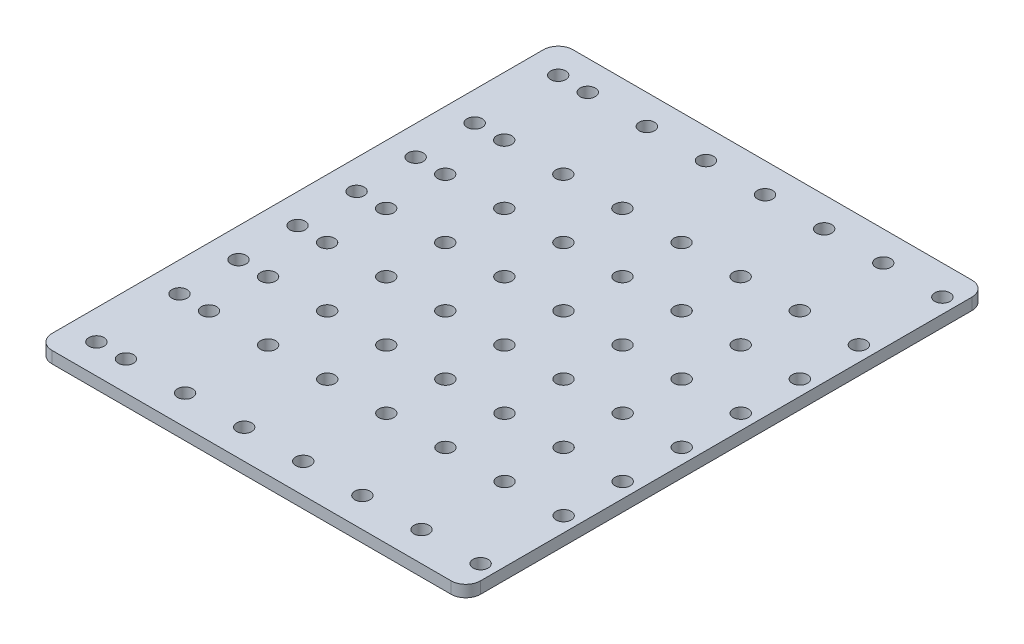
SolidWorks part; units mm, degrees
ref_plane "Front Plane" through (0, 0, 0) normal (0, 0, 1) x (1, 0, 0)
ref_plane "Top Plane" through (0, 0, 0) normal (0, 1, 0) x (1, 0, 0)
ref_plane "Right Plane" through (0, 0, 0) normal (1, 0, 0) x (0, 0, -1)
sketch "Sketch1" plane through (0, 0, 0) normal (0, 1, 0) x (1, 0, 0)
  line L0 (54, -9.0119) -> (54, -50009.0119) construction
  line L1 (-58, 70.5) -> (58, 70.5)
  line L2 (-58, 70.5) -> (-58, -70.5)
  line L3 (-58, -70.5) -> (58, -70.5)
  line L4 (58, 70.5) -> (58, -70.5)
  line L5 (-58, 70.5) -> (58, -70.5) construction
  line L6 (-58, -70.5) -> (58, 70.5) construction
  line L7 (17.5855, -62.5) -> (50017.5855, -62.5) construction
  line L8 (54, -62.5) -> (38, -62.5) construction
  line L9 (0, 0) -> (50000, 0) construction
  line L10 (-45.6818, -56) -> (49954.3182, -56) construction
  line L11 (-42, -56) -> (-26, -56) construction
  line L12 (-42, -62.5) -> (-50, -62.5) construction
  line L13 (-42.1091, 40) -> (-50.1091, 40) construction
  circle A0 centre (54, -62.5) radius 2.05
  circle A1 centre (38, -62.5) radius 2.05
  circle A2 centre (22, -62.5) radius 2.05
  circle A3 centre (6, -62.5) radius 2.05
  circle A4 centre (-10, -62.5) radius 2.05
  circle A5 centre (-26, -62.5) radius 2.05
  circle A6 centre (-42, -62.5) radius 2.05
  circle A7 centre (-42, 62.5) radius 2.05
  circle A8 centre (-26, 62.5) radius 2.05
  circle A9 centre (-10, 62.5) radius 2.05
  circle A10 centre (6, 62.5) radius 2.05
  circle A11 centre (22, 62.5) radius 2.05
  circle A12 centre (38, 62.5) radius 2.05
  circle A13 centre (54, 62.5) radius 2.05
  circle A14 centre (-42, -56) radius 2.05 construction
  circle A15 centre (-26, -56) radius 2.05 construction
  circle A16 centre (-10, -56) radius 2.05 construction
  circle A17 centre (6, -56) radius 2.05 construction
  circle A18 centre (22, -56) radius 2.05 construction
  circle A19 centre (38, -56) radius 2.05 construction
  circle A20 centre (54, -56) radius 2.05 construction
  circle A21 centre (-26.0182, -40) radius 2.05
  circle A22 centre (-10.0182, -40) radius 2.05
  circle A23 centre (5.9818, -40) radius 2.05
  circle A24 centre (21.9818, -40) radius 2.05
  circle A25 centre (37.9818, -40) radius 2.05
  circle A26 centre (53.9818, -40) radius 2.05
  circle A27 centre (-26.0364, -24) radius 2.05
  circle A28 centre (-10.0364, -24) radius 2.05
  circle A29 centre (5.9636, -24) radius 2.05
  circle A30 centre (21.9636, -24) radius 2.05
  circle A31 centre (37.9636, -24) radius 2.05
  circle A32 centre (53.9636, -24) radius 2.05
  circle A33 centre (-26.0546, -8) radius 2.05
  circle A34 centre (-10.0546, -8) radius 2.05
  circle A35 centre (5.9454, -8) radius 2.05
  circle A36 centre (21.9454, -8) radius 2.05
  circle A37 centre (37.9454, -8) radius 2.05
  circle A38 centre (53.9454, -8) radius 2.05
  circle A39 centre (-26.0728, 8) radius 2.05
  circle A40 centre (-10.0728, 8) radius 2.05
  circle A41 centre (5.9272, 8) radius 2.05
  circle A42 centre (21.9272, 8) radius 2.05
  circle A43 centre (37.9272, 8) radius 2.05
  circle A44 centre (53.9272, 8) radius 2.05
  circle A45 centre (-26.091, 24) radius 2.05
  circle A46 centre (-10.091, 24) radius 2.05
  circle A47 centre (5.909, 24) radius 2.05
  circle A48 centre (21.909, 24) radius 2.05
  circle A49 centre (37.909, 24) radius 2.05
  circle A50 centre (53.909, 24) radius 2.05
  circle A51 centre (-26.1091, 40) radius 2.05
  circle A52 centre (-10.1091, 40) radius 2.05
  circle A53 centre (5.8909, 40) radius 2.05
  circle A54 centre (21.8909, 40) radius 2.05
  circle A55 centre (37.8909, 40) radius 2.05
  circle A56 centre (53.8909, 40) radius 2.05
  circle A57 centre (-26.1273, 56) radius 2.05 construction
  circle A58 centre (-10.1273, 56) radius 2.05 construction
  circle A59 centre (5.8727, 56) radius 2.05 construction
  circle A60 centre (21.8727, 56) radius 2.05 construction
  circle A61 centre (37.8727, 56) radius 2.05 construction
  circle A62 centre (53.8727, 56) radius 2.05 construction
  circle A63 centre (-42.0182, -40) radius 2.05
  circle A64 centre (-42.0364, -24) radius 2.05
  circle A65 centre (-42.0546, -8) radius 2.05
  circle A66 centre (-42.0728, 8) radius 2.05
  circle A67 centre (-42.091, 24) radius 2.05
  circle A68 centre (-42.1091, 40) radius 2.05
  circle A69 centre (-42.1273, 56) radius 2.05 construction
  circle A70 centre (-50, -62.5) radius 2.05
  circle A71 centre (-50, -56) radius 2.05 construction
  circle A72 centre (-50.0182, -40) radius 2.05
  circle A73 centre (-50.0364, -24) radius 2.05
  circle A74 centre (-50.0546, -8) radius 2.05
  circle A75 centre (-50.0728, 8) radius 2.05
  circle A76 centre (-50.091, 24) radius 2.05
  circle A77 centre (-50.1273, 56) radius 2.05 construction
  circle A78 centre (-50, 62.5) radius 2.05
  circle A79 centre (-50.1091, 40) radius 2.05
  point P0 (0, 0)
  dimension "D5" = 4.1
  dimension "D1" = 141
  dimension "D2" = 116
  dimension "D3" = 8
  dimension "D4" = 4
  dimension "D7" = 16
  dimension "D8" = 6.5
  dimension "D11" = 16
  dimension "D13" = 8
  dimension "D15" = 8
  dimension "D6" = 7
  dimension "D9" = 7
  dimension "D10" = 8
  dimension "D12" = 2
  dimension "D14" = 2
extrude "Boss-Extrude1" add sketch "Sketch1" along normal blind 3.175
fillet "Fillet1" radius 4 4 edges at (58, 1.5875, -70.5) (-58, 1.5875, -70.5) (-58, 1.5875, 70.5) (58, 1.5875, 70.5)
equation "\"h\"= 141mm"
equation "\"w\"= 14 * 8 + 4"
equation "\"D1@Sketch1\"=\"h\""
equation "\"D2@Sketch1\"=\"w\""
